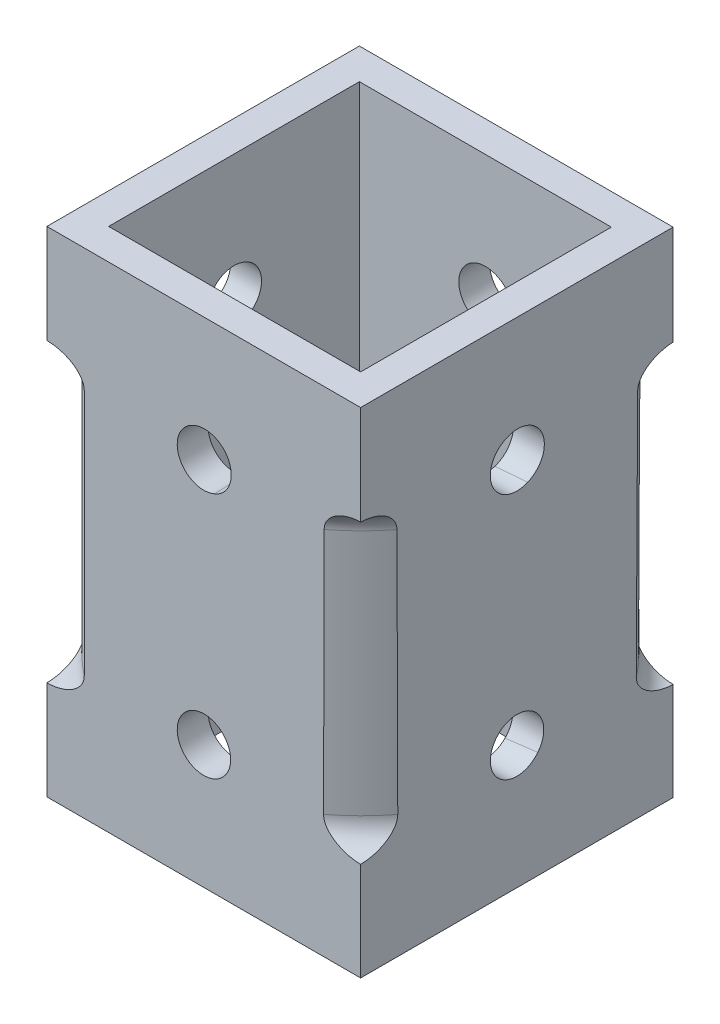
SolidWorks part; units mm, degrees
ref_plane "Front Plane" through (0, 0, 0) normal (0, 0, 1) x (1, 0, 0)
ref_plane "Top Plane" through (0, 0, 0) normal (0, 1, 0) x (1, 0, 0)
ref_plane "Right Plane" through (0, 0, 0) normal (1, 0, 0) x (0, 0, -1)
sketch "Sketch1" plane through (0, 0, 0) normal (0, 1, 0) x (1, 0, 0)
  line L0 (12.7, 12.65) -> (-12.7, 12.65)
  line L1 (10.2, -10.15) -> (-10.2, -10.15)
  line L2 (10.2, -10.15) -> (10.2, 10.15)
  line L3 (10.2, 10.15) -> (-10.2, 10.15)
  line L4 (-10.2, -10.15) -> (-10.2, 10.15)
  line L5 (10.2, -10.15) -> (-10.2, 10.15) construction
  line L6 (10.2, 10.15) -> (-10.2, -10.15) construction
  line L7 (-12.7, -12.65) -> (-12.7, 12.65)
  line L8 (12.7, -12.65) -> (-12.7, -12.65)
  line L9 (12.7, -12.65) -> (12.7, 12.65)
  point P0 (0, 0)
  dimension "D1" = 20.4
  dimension "D2" = 20.3
  dimension "D3" = 2.5
extrude "Boss-Extrude1" add sketch "Sketch1" along normal blind 40
ref_plane "Plane1" through (0, 0, 0) normal (0.7057, 0, 0.7085) x (0.7085, 0, -0.7057)
sketch "Sketch2" plane through (0, 0, 0) normal (0.7057, 0, 0.7085) x (0.7085, 0, -0.7057)
  line L0 (-17.9252, 10) -> (-17.9252, 30) construction
  line L1 (-17.9252, 40) -> (-17.9252, 0) construction
  line L2 (-19.9252, 10) -> (-19.9252, 30)
  line L3 (-15.9252, 10) -> (-15.9252, 30)
  line L4 (0.0707, 40) -> (0, 0) construction
  arc A0 (-19.9252, 10) -> (-15.9252, 10) centre (-17.9252, 10) ccw
  arc A1 (-15.9252, 30) -> (-19.9252, 30) centre (-17.9252, 30) ccw
  point P4 (-17.9252, 20)
  dimension "D2" = 2
  dimension "D1" = 20
revolve "Cut-Revolve1" cut sketch "Sketch2" angle 360 about L4
sketch "Sketch3" plane through (0, 0, -10.15) normal (0, 0, 1) x (1, 0, 0)
  line L0 (0, 0) -> (0, 40) construction
  circle A0 centre (0, 30) radius 2.15
  circle A1 centre (0, 10) radius 2.15
  point P11 (0, 20)
  dimension "D3" = 4.3
  dimension "D1" = 10
  dimension "D2" = 10
  dimension "D4" = 40
extrude "Cut-Extrude1" cut sketch "Sketch3" against normal blind 40 and the other way blind 40
pattern_circular "CirPattern1" count 4 over 360 about axis through (0.0501, 40, -0.0499) along (-0.0013, -1, 0.0012) of "Cut-Extrude1"
